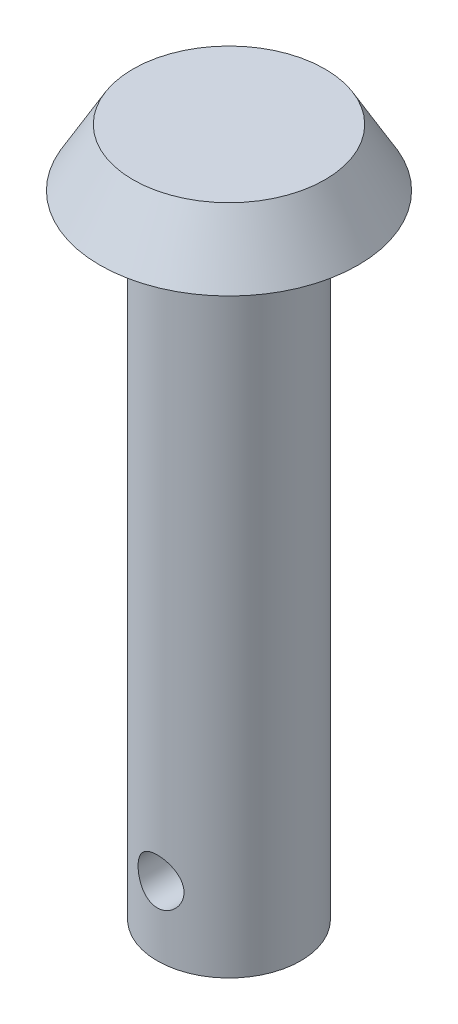
SolidWorks part; units mm, degrees
ref_plane "Front Plane" through (0, 0, 0) normal (0, 0, 1) x (1, 0, 0)
ref_plane "Top Plane" through (0, 0, 0) normal (0, 1, 0) x (1, 0, 0)
ref_plane "Right Plane" through (0, 0, 0) normal (1, 0, 0) x (0, 0, -1)
sketch "Sketch1" plane through (0, 0, 0) normal (0, 1, 0) x (1, 0, 0)
  circle A0 centre (0, 0) radius 12.5
  dimension "D1" = 25
extrude "Boss-Extrude1" add sketch "Sketch1" along normal blind 110
sketch "Sketch2" plane through (0, 110, 0) normal (0, 1, 0) x (1, 0, 0)
  circle A0 centre (0, 0) radius 22.5
  dimension "D1" = 45
extrude "Boss-Extrude2" add sketch "Sketch2" along normal blind 10 draft 30
sketch "Sketch3" plane through (0, 0, 0) normal (0, 0, 1) x (1, 0, 0)
  line L0 (-12.5, 0) -> (12.5, 0) construction
  line L1 (12.5, 0) -> (12.5, 110) construction
  circle A0 centre (0, 12) radius 4
  dimension "D1" = 8
  dimension "D2" = 12
  dimension "D3" = 12.5
extrude "Cut-Extrude1" cut sketch "Sketch3" against normal mid plane 60
